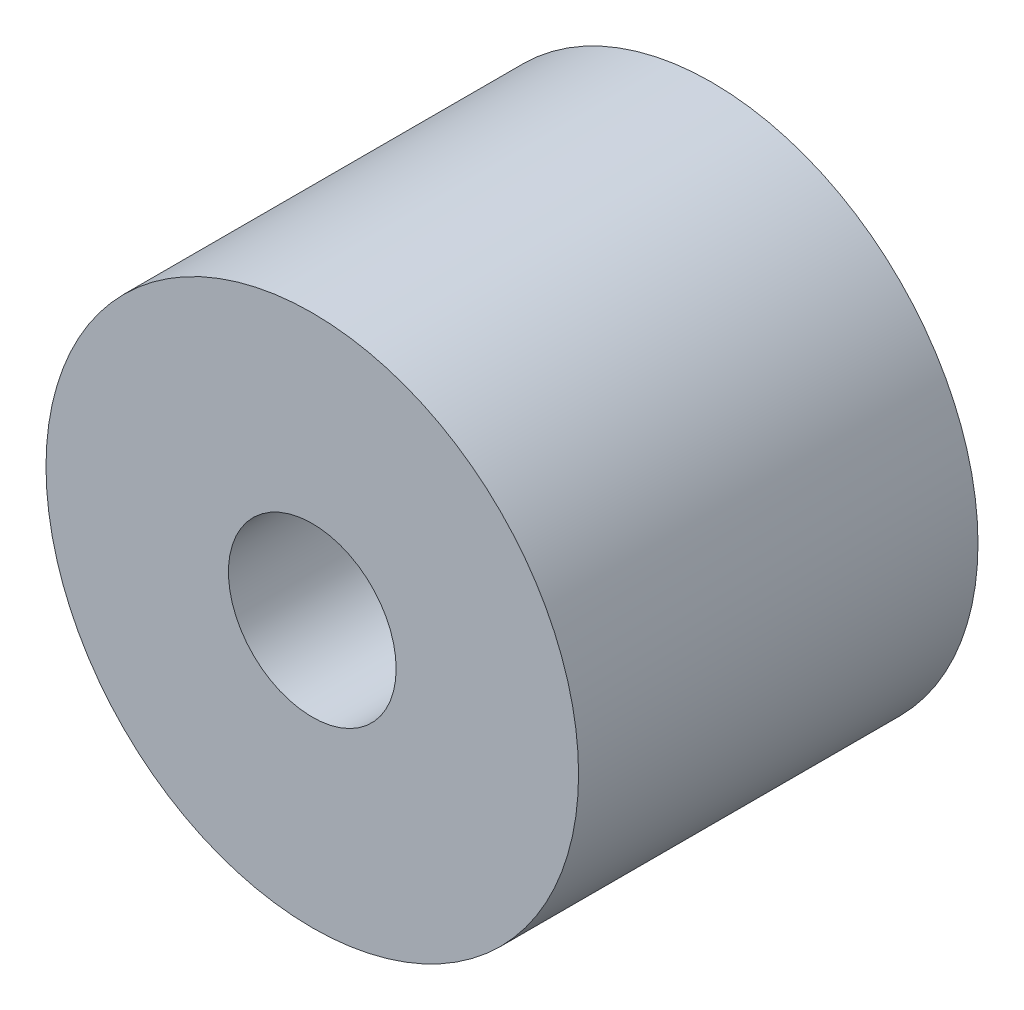
SolidWorks part; units mm, degrees
material "AISI 304"
ref_plane "Front" through (0, 0, 0) normal (0, 0, 1) x (1, 0, 0)
ref_plane "Top" through (0, 0, 0) normal (0, 1, 0) x (1, 0, 0)
ref_plane "Right" through (0, 0, 0) normal (1, 0, 0) x (0, 0, -1)
sketch "Sketch1" plane through (0, 0, 0) normal (0, 0, 1) x (1, 0, 0)
  circle A0 centre (0, 0) radius 6.35
  circle A1 centre (0, 0) radius 4.7625
  dimension "RollerOD" = 12.7
  dimension "RollerID" = 9.525
extrude "Boss-Extrude1" add sketch "Sketch1" along normal blind 9.525
sketch "Sketch2" plane through (0, 0, 9.525) normal (0, 0, 1) x (1, 0, 0)
  circle A0 centre (0, 0) radius 4.7625 construction
  circle A1 centre (0, 0) radius 4.7625
  circle A2 centre (0, 0) radius 2
  dimension "BoreDia" = 4
extrude "Boss-Extrude2" add sketch "Sketch2" against normal up to surface (9.525 mm away) up to face at (6.35, 0, 0)
sketch "Sketch3" plane through (0, 0, 0) normal (0, 0, -1) x (-1, 0, 0)
  circle A0 centre (0, 0) radius 4
  circle A1 centre (0, 0) radius 2 construction
  circle A2 centre (0, 0) radius 2
  dimension "HubOD" = 8
extrude "Boss-Extrude3" [suppressed] add sketch "Sketch3" along normal blind 6.35
